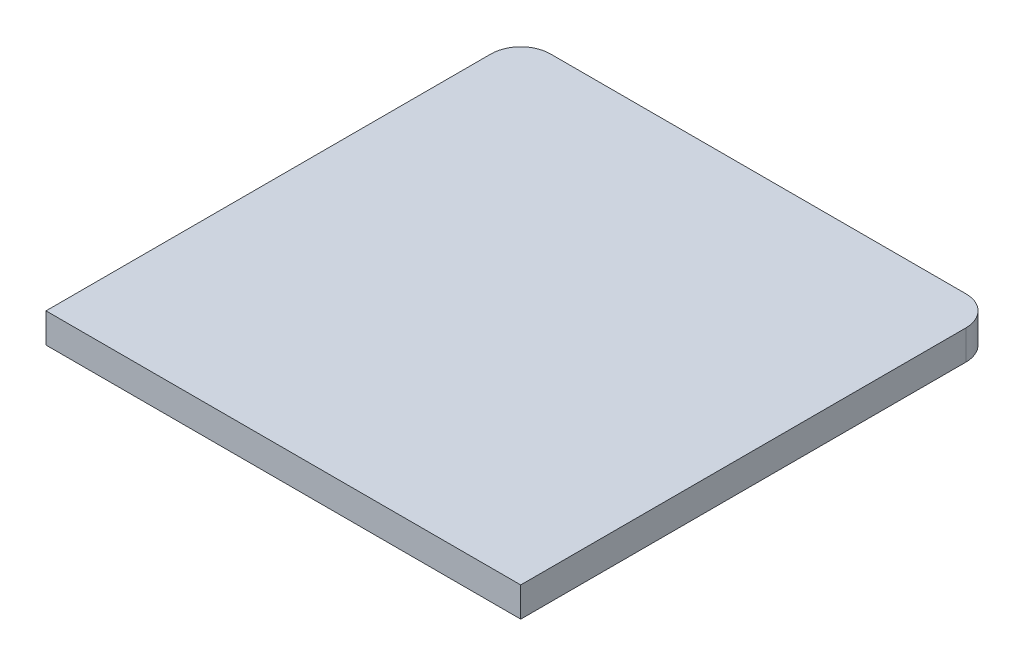
SolidWorks part; units mm, degrees
ref_plane "Front Plane" through (0, 0, 0) normal (0, 0, 1) x (1, 0, 0)
ref_plane "Top Plane" through (0, 0, 0) normal (0, 1, 0) x (1, 0, 0)
ref_plane "Right Plane" through (0, 0, 0) normal (1, 0, 0) x (0, 0, -1)
sketch "Sketch1" plane through (0, 0, 0) normal (0, 1, 0) x (1, 0, 0)
  line L1 (0, 0) -> (50.8, 0)
  line L2 (0, 0) -> (0, 50.8)
  line L3 (0, 50.8) -> (50.8, 50.8)
  line L4 (50.8, 0) -> (50.8, 50.8)
  dimension "D1" = 50.8
  dimension "D2" = 50.8
extrude "Boss-Extrude1" add sketch "Sketch1" along normal blind 3.175 contours L2 L3 L4 L1
fillet "Fillet1" radius 3.175 2 edges at (0, 1.5875, -50.8) (50.8, 1.5875, -50.8)
